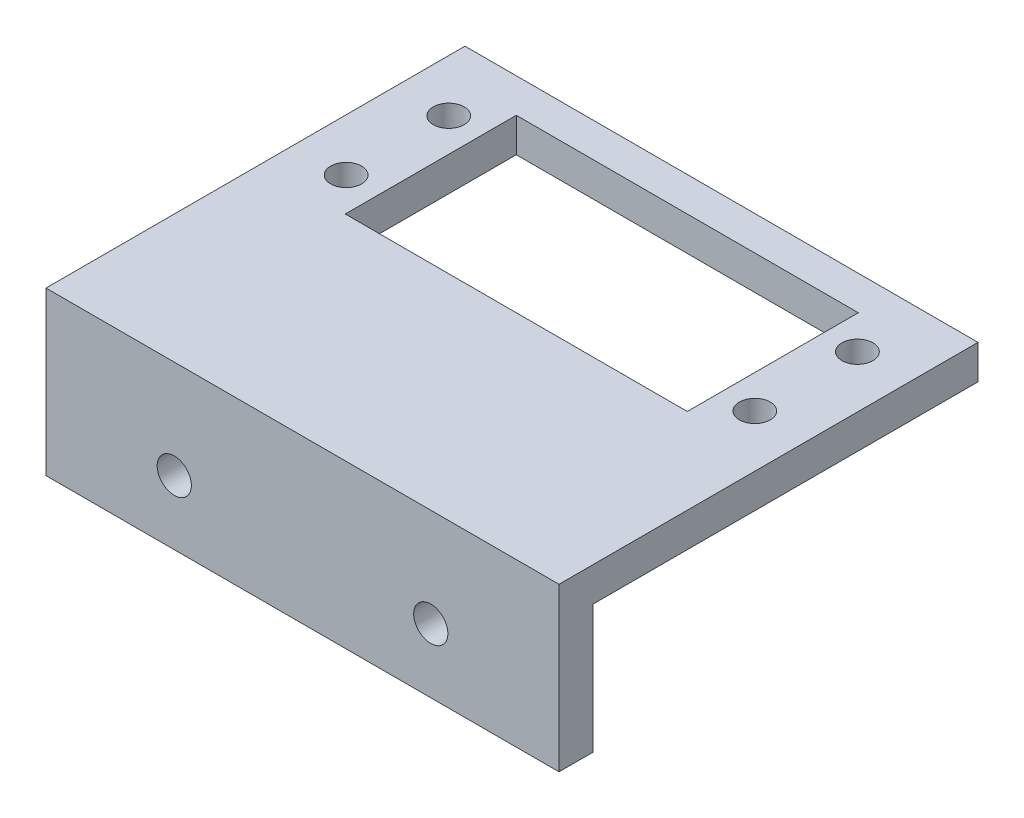
SolidWorks part; units mm, degrees
material "1060 Alloy"
ref_plane "Front Plane" through (0, 0, 0) normal (0, 0, 1) x (1, 0, 0)
ref_plane "Top Plane" through (0, 0, 0) normal (0, 1, 0) x (1, 0, 0)
ref_plane "Right Plane" through (0, 0, 0) normal (1, 0, 0) x (0, 0, -1)
sketch "Sketch1" plane through (0, 0, 0) normal (0, 0, 1) x (1, 0, 0)
  line L1 (-30, -25) -> (30, -25)
  line L2 (-30, -25) -> (-30, 25)
  line L3 (-30, 25) -> (30, 25)
  line L4 (30, -25) -> (30, 25)
  line L5 (-30, -25) -> (30, 25) construction
  line L6 (-30, 25) -> (30, -25) construction
  point P0 (0, 0)
  dimension "D1" = 60
  dimension "D2" = 50
extrude "Boss-Extrude1" add sketch "Sketch1" along normal blind 4
sketch "Sketch2" plane through (0, 0, 0) normal (0, 0, -1) x (-1, 0, 0)
  line L0 (30, 25) -> (30, -25) construction
  line L1 (-30, 25) -> (30, 25)
  line L2 (-30, 25) -> (-30, 21)
  line L3 (-30, 21) -> (30, 21)
  line L4 (30, 25) -> (30, 21)
  dimension "D1" = 4
extrude "Boss-Extrude2" add sketch "Sketch2" along normal blind 45
sketch "Sketch3" plane through (0, 25, 0) normal (0, 1, 0) x (1, 0, 0)
  line L0 (-30, -4) -> (-30, 45) construction
  line L1 (-20, 21) -> (20, 21)
  line L2 (-20, 21) -> (-20, 41)
  line L3 (-20, 41) -> (20, 41)
  line L4 (20, 21) -> (20, 41)
  line L5 (-20, 21) -> (20, 41) construction
  line L6 (-20, 41) -> (20, 21) construction
  line L8 (30, -4) -> (-30, -4) construction
  point P0 (0, 31)
  dimension "D1" = 40
  dimension "D2" = 20
  dimension "D3" = 10
  dimension "D4" = 25
extrude "Cut-Extrude1" cut sketch "Sketch3" against normal blind 60
sketch "Sketch4" plane through (0, 0, 0) normal (0, 0, -1) x (-1, 0, 0)
  line L0 (30, 25) -> (30, 6)
  line L1 (30, 21) -> (30, -25) construction
  line L2 (30, 6) -> (-30, 6)
  line L3 (-30, -25) -> (-30, 21) construction
  line L4 (-30, 6) -> (-30, 25)
  line L5 (-30, 25) -> (30, 25)
  line M6 (-30, 21) -> (-30, -25)
  line M7 (-30, -25) -> (30, -25)
  line M8 (30, -25) -> (30, 21)
  dimension "D1" = 19
extrude "Cut-Extrude2" cut sketch "Sketch4" against normal blind 10 contours L2 M8 M6 M7
sketch "Sketch5" plane through (0, 0, 0) normal (0, 0, -1) x (-1, 0, 0)
  line L0 (-30, 6) -> (-30, 21) construction
  line L1 (30, 6) -> (-30, 6) construction
  circle A0 centre (-15, 13.5) radius 2
  circle A1 centre (15, 13.5) radius 2
  dimension "D1" = 4
  dimension "D2" = 4
  dimension "D3" = 30
  dimension "D4" = 15
  dimension "D5" = 7.5
extrude "Cut-Extrude3" cut sketch "Sketch5" against normal through all
sketch "Sketch6" plane through (0, 25, 0) normal (0, 1, 0) x (1, 0, 0)
  line L0 (20, 21) -> (20, 41) construction
  line L1 (-20, 21) -> (20, 21) construction
  circle A0 centre (23.9, 25) radius 1.81
  circle A1 centre (23.9, 37) radius 1.81
  dimension "D1" = 3.62
  dimension "D2" = 3.62
  dimension "D3" = 12
  dimension "D4" = 3.9
  dimension "D5" = 4
extrude "Cut-Extrude4" cut sketch "Sketch6" against normal blind 10
sketch "Sketch7" plane through (0, 25, 0) normal (0, 1, 0) x (1, 0, 0)
  line L0 (20, 41) -> (-20, 41) construction
  line L1 (-20, 41) -> (-20, 21) construction
  circle A0 centre (-23.9, 37) radius 1.81
  circle A1 centre (-23.9, 25) radius 1.81
  dimension "D1" = 3.62
  dimension "D2" = 3.62
  dimension "D3" = 12
  dimension "D4" = 4
  dimension "D5" = 3.9
extrude "Cut-Extrude5" cut sketch "Sketch7" against normal through all
